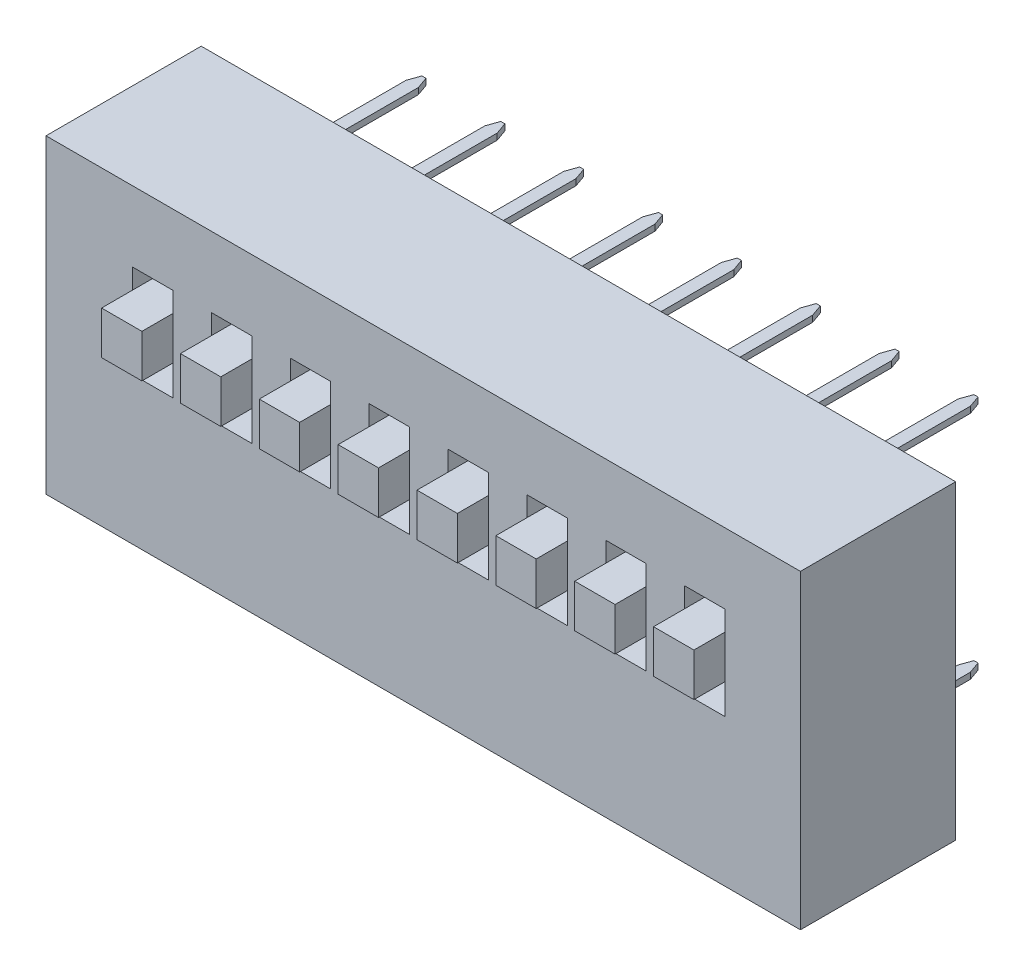
SolidWorks part; units mm, degrees
ref_plane "Front Plane" through (0, 0, 0) normal (0, 0, 1) x (1, 0, 0)
ref_plane "Top Plane" through (0, 0, 0) normal (0, 1, 0) x (1, 0, 0)
ref_plane "Right Plane" through (0, 0, 0) normal (1, 0, 0) x (0, 0, -1)
sketch "Sketch1" plane through (0, 0, 0) normal (0, 0, 1) x (1, 0, 0)
  line L1 (-12.15, -5) -> (12.15, -5)
  line L2 (-12.15, -5) -> (-12.15, 5)
  line L3 (-12.15, 5) -> (12.15, 5)
  line L4 (12.15, -5) -> (12.15, 5)
  line L5 (-12.15, -5) -> (12.15, 5) construction
  line L6 (-12.15, 5) -> (12.15, -5) construction
  point P0 (0, 0)
  dimension "D1" = 10
  dimension "D2" = 24.3
extrude "Boss-Extrude1" add sketch "Sketch1" along normal blind 5
sketch "Sketch2" plane through (0, 0, 5) normal (0, 0, 1) x (1, 0, 0)
  line L1 (-9.3603, 2.7331) -> (-8.0603, 2.7331)
  line L2 (-9.3603, 2.7331) -> (-9.3603, -0.2669)
  line L3 (-9.3603, -0.2669) -> (-8.0603, -0.2669)
  line L4 (-8.0603, 2.7331) -> (-8.0603, -0.2669)
  line L5 (-9.3603, 2.7331) -> (-8.0603, -0.2669) construction
  line L6 (-9.3603, -0.2669) -> (-8.0603, 2.7331) construction
  point P0 (-8.7103, 1.2331)
  point P5 (-8.7103, 1.2331)
  dimension "D1" = 3
  dimension "D2" = 1.3
extrude "Cut-Extrude3" cut sketch "Sketch2" against normal blind 1
pattern_linear "LPattern1" count 8 spacing 2.54 along (1, 0, 0) of "Cut-Extrude3"
sketch "Sketch3" plane through (0, 0, 4) normal (0, 0, 1) x (1, 0, 0)
  line L0 (-8.0603, -0.2669) -> (-8.0603, 2.7331) construction
  line L1 (-9.3603, 2.0904) -> (-8.0603, 2.0904)
  line L2 (-9.3603, 2.0904) -> (-9.3603, 0.7064)
  line L3 (-9.3603, 0.7064) -> (-8.0603, 0.7064)
  line L4 (-8.0603, 2.0904) -> (-8.0603, 0.7064)
  line L5 (-9.3603, 2.0904) -> (-8.0603, 0.7064) construction
  line L6 (-9.3603, 0.7064) -> (-8.0603, 2.0904) construction
  line L7 (-9.3603, 2.7331) -> (-9.3603, -0.2669) construction
  point P0 (-8.7103, 1.3984)
  point P7 (-9.3603, 2.0904)
extrude "Boss-Extrude2" add sketch "Sketch3" along normal blind 2
pattern_linear "LPattern2" count 8 spacing 2.54 along (1, 0, 0) of "Boss-Extrude2"
move or copy body "Body-Move/Copy1" bodies to move or copy 105 copy no translate (0, 0, 0.9)
ref_plane "Plane1" through (0, 3.81, 0) normal (0, 1, 0) x (1, 0, 0)
sketch "Sketch4" plane through (0, 3.81, 0) normal (0, 1, 0) x (1, 0, 0)
  line L0 (-8.89, -0.9) -> (-8.89, 3.0142) construction
  line L1 (12.15, -0.9) -> (-12.15, -0.9) construction
  line L2 (8.89, -0.9) -> (8.89, 3.9198) construction
  line L3 (-8.89, -0.9) -> (-12.15, -0.9) construction
  line L4 (8.89, -0.9) -> (12.15, -0.9) construction
  line L5 (-9.39, -0.9) -> (-9.39, 0)
  line L6 (-9.39, 0) -> (-9.09, 0)
  line L7 (-9.09, 0) -> (-9.09, 2.6343)
  line L8 (-9.09, 2.6343) -> (-8.9557, 3.0142)
  line L9 (-8.8243, 3.0142) -> (-8.69, 2.6343)
  line L10 (-8.69, 2.6343) -> (-8.69, 0)
  line L11 (-8.69, 0) -> (-8.39, 0)
  line L12 (-8.39, 0) -> (-8.39, -0.9)
  line L13 (-8.39, -0.9) -> (-9.39, -0.9)
  line L14 (-8.9557, 3.0142) -> (-8.8243, 3.0142)
  line L15 (-8.89, 3.2) -> (-8.89, 4.8032) construction
  dimension "D1" = 17.78
  dimension "D2" = 3.2
  dimension "D3" = 0.9
  dimension "D4" = 0.9
  dimension "D5" = 0.2
  dimension "D6" = 0.2
  dimension "D7" = 0.6
  dimension "D8" = 0.6
  dimension "D9" = 1
extrude "Boss-Extrude3" add sketch "Sketch4" against normal blind 0.2
pattern_linear "LPattern3" count 8 spacing 2.54 along (1, 0, 0) of "Boss-Extrude3"
mirror "Mirror1" about plane through (0, 0, 0) normal (0, 1, 0) of "Boss-Extrude3"
pattern_linear "LPattern5" count 8 spacing 2.54 along (1, 0, 0) skipping (1, 0), (2, 0), (3, 0), (4, 0), (5, 0), (6, 0) of "Mirror1"
